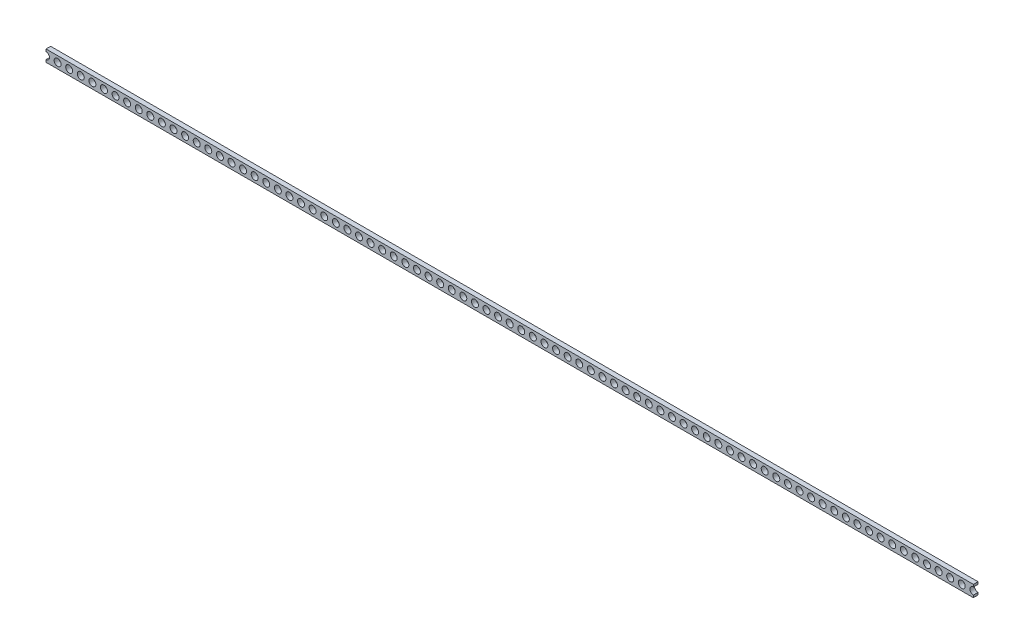
SolidWorks part; units mm, degrees
ref_plane "前视基准面" through (0, 0, 0) normal (0, 0, 1) x (1, 0, 0)
ref_plane "上视基准面" through (0, 0, 0) normal (0, 1, 0) x (1, 0, 0)
ref_plane "右视基准面" through (0, 0, 0) normal (1, 0, 0) x (0, 0, -1)
sketch "草图1" plane through (0, 0, 0) normal (0, 0, 1) x (1, 0, 0)
  line L1 (0, 0) -> (400, 0)
  line L2 (0, 0) -> (0, -5)
  line L3 (0, -5) -> (400, -5)
  line L4 (400, 0) -> (400, -5)
  dimension "D1" = 5
  dimension "D2" = 400
extrude "凸台-拉伸1" add sketch "草图1" along normal blind 2
sketch "草图2" plane through (0, 0, 2) normal (0, 0, 1) x (1, 0, 0)
  line L0 (400, 0) -> (0, 0) construction
  line L1 (200, 0) -> (200, -5) construction
  line L2 (0, -5) -> (400, -5) construction
  circle A0 centre (200, -2.5) radius 1.5
  dimension "D1" = 3
extrude "切除-拉伸1" cut sketch "草图2" against normal through all
pattern_linear "阵列(线性)1" count 41 spacing 5 along (1, 0, 0) of "切除-拉伸1"
pattern_linear "阵列(线性)2" count 41 spacing 5 along (-1, 0, 0) of "切除-拉伸1"
